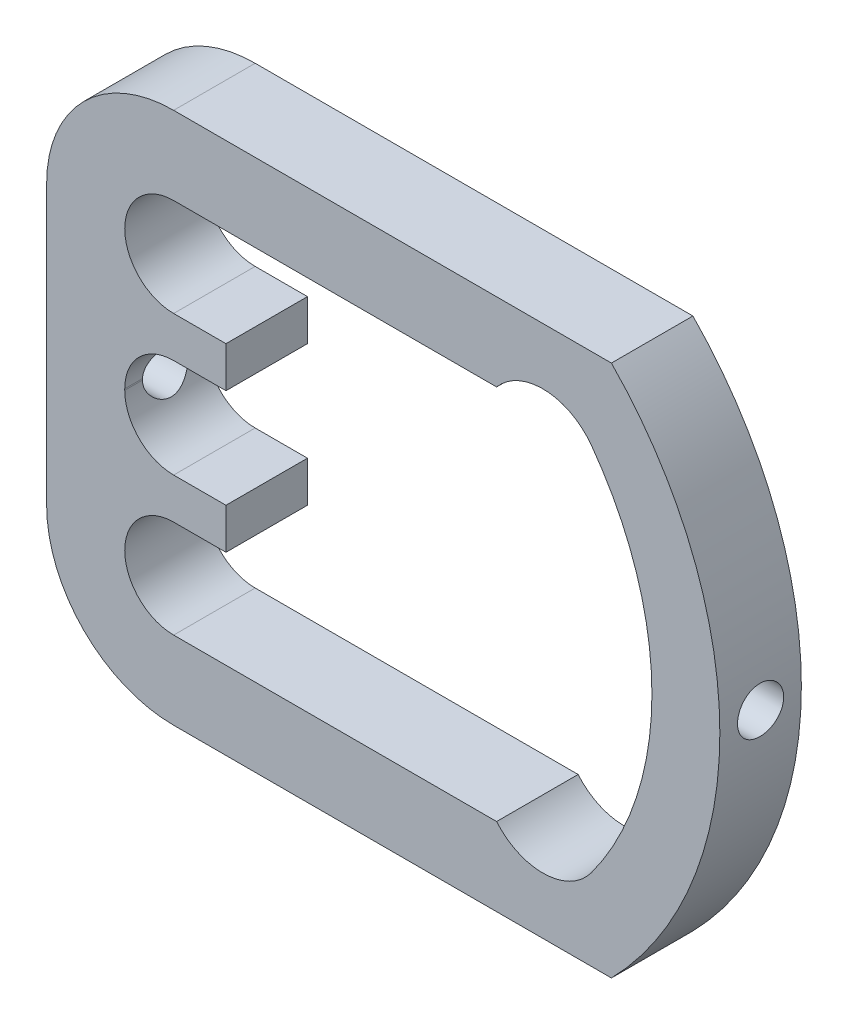
SolidWorks part; units mm, degrees
ref_plane "前视基准面" through (0, 0, 0) normal (0, 0, 1) x (1, 0, 0)
ref_plane "上视基准面" through (0, 0, 0) normal (0, 1, 0) x (1, 0, 0)
ref_plane "右视基准面" through (0, 0, 0) normal (1, 0, 0) x (0, 0, -1)
sketch "草图1" plane through (0, 0, 0) normal (0, 0, 1) x (1, 0, 0)
  line L0 (-314.3551, 0) -> (15403.4009, 0) construction
  line L1 (3.7755, 4.4995) -> (11.6217, 13.8502)
  line L2 (8.9406, 19.6) -> (-8, 19.6)
  line L3 (-8, 19.6) -> (-8, -19.6) construction
  line L4 (8.9406, -19.6) -> (-8, -19.6)
  line L5 (3.7755, -4.4995) -> (11.6217, -13.8502)
  line L6 (-8, 19.6) -> (-12.15, 19.6)
  line L7 (-52.8584, -11.6) -> (-16, -11.6) construction
  line L8 (-52.8584, -11.6) -> (-52.8584, 11.6) construction
  line L9 (-52.8584, 11.6) -> (-16, 11.6) construction
  line L10 (-16, -11.6) -> (-16, 11.6) construction
  line L11 (-52.8584, -11.6) -> (-16, 11.6) construction
  line L12 (-52.8584, 11.6) -> (-16, -11.6) construction
  line L13 (-36, -19.6) -> (-21.5, -19.6) construction
  line L14 (-12.15, -19.6) -> (-8, -19.6)
  line L15 (-36, 11.6) -> (-27.6, 11.6) construction
  line L16 (-16, -19.6) -> (-52.8584, -19.6) construction
  line L17 (-16, -19.6) -> (-16, 19.6) construction
  line L18 (-16, 19.6) -> (-52.8584, 19.6) construction
  line L19 (-52.8584, -19.6) -> (-52.8584, 19.6) construction
  line L20 (-16, -19.6) -> (-52.8584, 19.6) construction
  line L21 (-16, 19.6) -> (-52.8584, -19.6) construction
  line L22 (-31, -1000) -> (-31, 49000) construction
  line L23 (-36, 19.6) -> (-21.5, 19.6) construction
  line L24 (8.9406, 19.6) -> (20.0716, 19.6)
  line L25 (8.9406, -19.6) -> (20.0716, -19.6)
  line L26 (-27.6, -11.6) -> (-36, -11.6) construction
  line L27 (11.6217, -13.8502) -> (-8, -13.8502)
  line L28 (-8.3, -6.6498) -> (-8.3, -3.6498)
  line L29 (-7.6629, 13.8502) -> (11.6217, 13.8502)
  line L30 (11.6217, 13.8502) -> (11.4839, 13.9897)
  line L31 (-21.5, -10.25) -> (-21.5, 10.25)
  line L32 (-15.7502, -0.0495) -> (-15.7502, 0.0495)
  line L33 (-12.15, 13.8502) -> (-7.6629, 13.8502)
  line L35 (-8, -13.8502) -> (-12.15, -13.8502)
  line L36 (-12.15, -6.6498) -> (-8.3, -6.6498)
  line L37 (-12.15, 6.6498) -> (-8.3, 6.6498)
  line L38 (-12.15, -3.6498) -> (-8.3, -3.6498)
  line L39 (-12.15, 3.6498) -> (-8.3, 3.6498)
  line L40 (-8.3, 3.6498) -> (-8.3, 6.6498)
  circle A0 centre (0, 0) radius 23.0541 construction
  circle A1 centre (0, 0) radius 28.0541 construction
  circle A2 centre (-36, 15.6) radius 2 construction
  circle A3 centre (-36, 15.6) radius 3.2 construction
  arc A4 (-36, 19.6) -> (-36, 11.6) centre (-36, 15.6) ccw construction
  arc A5 (3.7755, 4.4995) -> (3.7755, -4.4995) centre (9.1379, 0) ccw construction
  arc A6 (8.9406, -19.6) -> (11.6217, -13.8502) centre (8.9406, -16.1) ccw
  arc A7 (11.6217, 13.8502) -> (8.9406, 19.6) centre (8.9406, 16.1) ccw
  arc A8 (-36, -19.6) -> (-36, -11.6) centre (-36, -15.6) cw construction
  arc A9 (-27.6, -11.6) -> (-27.6, 11.6) centre (-27.6, 0) ccw construction
  circle A10 centre (-36, -15.6) radius 2 construction
  circle A11 centre (-36, -15.6) radius 3.2 construction
  circle A12 centre (13.0541, 0) radius 10 construction
  arc A13 (20.0716, 19.6) -> (20.0716, -19.6) centre (0, 0) cw
  arc A14 (18.6012, 13.6194) -> (11.6217, 13.8502) centre (15.0209, 10.998) ccw
  arc A15 (18.6012, -13.6194) -> (11.6217, -13.8502) centre (15.0209, -10.998) cw
  arc A16 (18.6012, 13.6194) -> (18.6012, -13.6194) centre (0, 0) cw
  arc A17 (-12.15, -19.6) -> (-21.5, -10.25) centre (-12.15, -10.25) cw
  arc A18 (-21.5, 10.25) -> (-12.15, 19.6) centre (-12.15, 10.25) cw
  arc A19 (-12.15, -6.6498) -> (-12.15, -13.8502) centre (-12.15, -10.25) ccw
  arc A20 (-12.15, 13.8502) -> (-12.15, 6.6498) centre (-12.15, 10.25) ccw
  arc A21 (-15.7502, -0.0495) -> (-12.15, -3.6498) centre (-12.15, -0.0495) ccw
  arc A22 (-15.7502, 0.0495) -> (-12.15, 3.6498) centre (-12.15, 0.0495) cw
  point P8 (-8, 0)
  point P9 (-34.4292, 0)
  point P18 (-34.4292, 0)
  point P38 (16.4464, -19.6)
  point P41 (16.4464, 19.6)
  dimension "D3" = 5
  dimension "D7" = 4
  dimension "D8" = 6.4
  dimension "D13" = 7
  dimension "D14" = 3.5
  dimension "D15" = 20
  dimension "D16" = 0.6
  dimension "D17" = 3
  dimension "D18" = 9.35
  dimension "D1" = 23.2
  dimension "D2" = 100
  dimension "D4" = 8
  dimension "D5" = 5.5
  dimension "D6" = 8
  dimension "D9" = 4
  dimension "D10" = 8
  dimension "D11" = 15
  dimension "D12" = 5
extrude "凸台-拉伸1" add sketch "草图1" along normal blind 6
sketch "草图2" plane through (0, 0, 0) normal (1, 0, 0) x (0, 0, -1)
  circle A0 centre (-3, -0.0495) radius 1.7
  dimension "D1" = 3.4
  dimension "D2" = 3
extrude "切除-拉伸1" cut sketch "草图2" along normal through all and the other way through all
